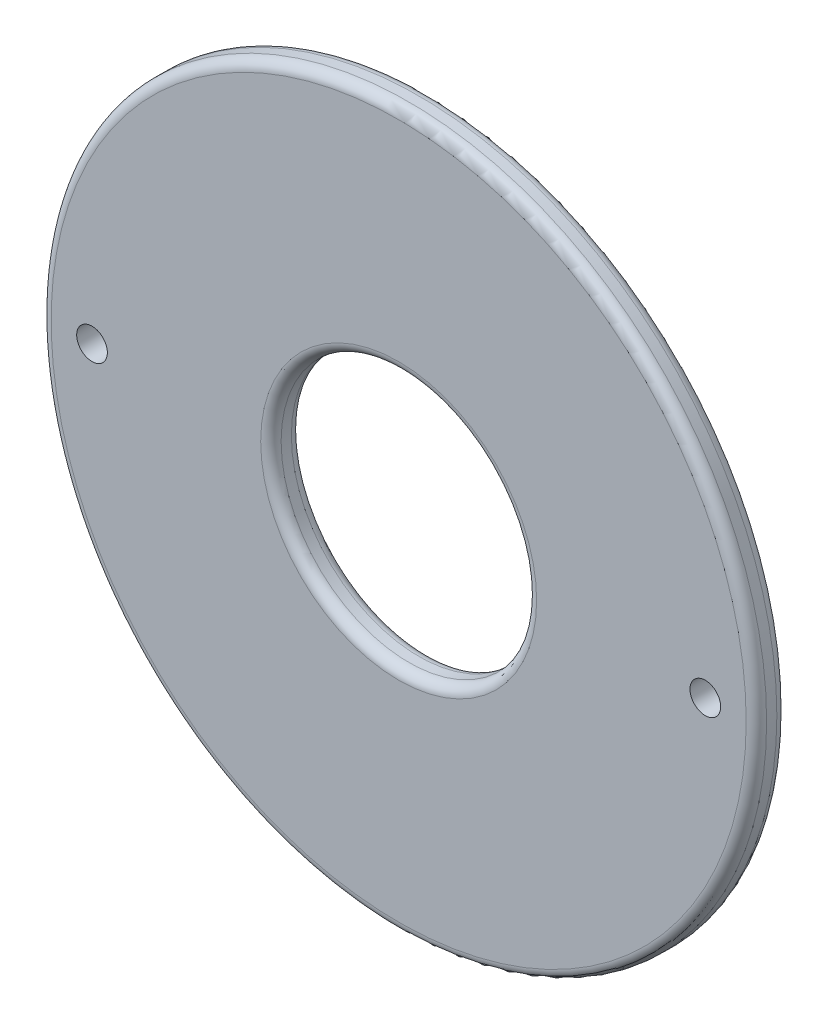
SolidWorks part; units mm, degrees
material "PETG"
ref_plane "Alzado" through (0, 0, 0) normal (0, 0, 1) x (1, 0, 0)
ref_plane "Planta" through (0, 0, 0) normal (0, 1, 0) x (1, 0, 0)
ref_plane "Vista lateral" through (0, 0, 0) normal (1, 0, 0) x (0, 0, -1)
sketch "Croquis1" plane through (0, 0, 0) normal (0, 0, 1) x (1, 0, 0)
  circle A0 centre (0, 0) radius 35
  circle A1 centre (0, 0) radius 12.5
  circle A2 centre (30, 0) radius 1.5
  circle A3 centre (-30, 0) radius 1.5
  dimension "D3" = 3
  dimension "D4" = 3
  dimension "D5" = 70
  dimension "D6" = 25
  dimension "D1" = 30
  dimension "D2" = 60
extrude "Saliente-Extruir1" add sketch "Croquis1" along normal blind 3
fillet "Redondeo1" radius 1 4 edges at (12.5, 0, 3) (12.5, 0, 0) (35, 0, 0) (35, 0, 3)
